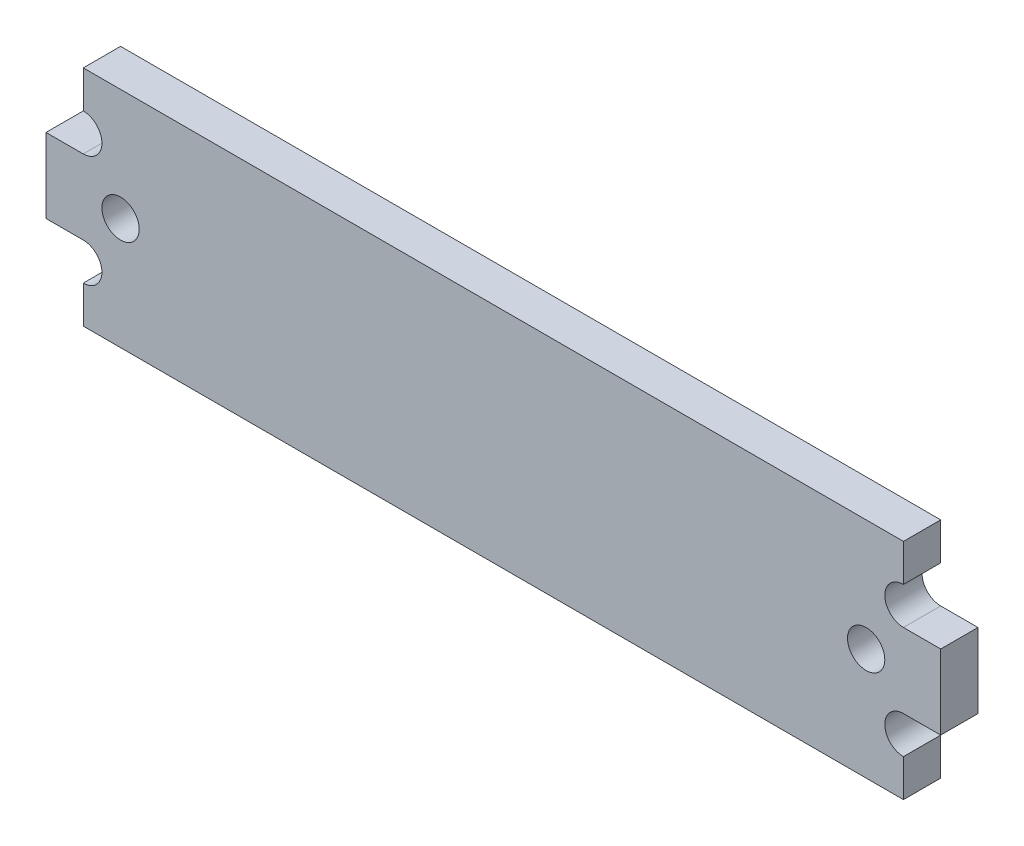
SolidWorks part; units mm, degrees
material "自訂玻璃纖維"
ref_plane "前基準面" through (0, 0, 0) normal (0, 0, 1) x (1, 0, 0)
ref_plane "上基準面" through (0, 0, 0) normal (0, 1, 0) x (1, 0, 0)
ref_plane "右基準面" through (0, 0, 0) normal (1, 0, 0) x (0, 0, -1)
sketch "草圖1" plane through (0, 0, 0) normal (0, 0, 1) x (1, 0, 0)
  line L0 (-31.3907, -5.425) -> (-31.3907, -7.425)
  line L1 (-31.3907, 4.575) -> (12.6093, 4.575)
  line L2 (-31.3907, 4.575) -> (-31.3907, 2.575)
  line L3 (-31.3907, -7.425) -> (12.6093, -7.425)
  line L4 (12.6093, 4.575) -> (12.6093, 2.575)
  line L5 (-31.3907, 0.575) -> (-33.3907, 0.575)
  line L6 (12.6093, -5.425) -> (12.6093, -7.425)
  line L7 (-31.3907, -3.425) -> (-33.3907, -3.425)
  line L8 (-33.3907, 0.575) -> (-33.3907, -3.425)
  line L9 (14.6093, 0.575) -> (14.6093, -3.425)
  line L10 (12.6093, -3.425) -> (14.6093, -3.425)
  line L11 (12.6093, 0.575) -> (14.6093, 0.575)
  arc A0 (-31.3907, 0.575) -> (-31.3907, 2.575) centre (-31.3907, 1.575) ccw
  arc A1 (-31.3907, -3.425) -> (-31.3907, -5.425) centre (-31.3907, -4.425) cw
  arc A2 (12.6093, -3.425) -> (12.6093, -5.425) centre (12.6093, -4.425) ccw
  arc A3 (12.6093, 0.575) -> (12.6093, 2.575) centre (12.6093, 1.575) cw
  circle A4 centre (-29.3907, -1.425) radius 1
  circle A5 centre (10.6093, -1.425) radius 1
  point P6 (12.6093, 4.575)
  point P11 (-31.3907, -7.425)
  point P14 (-31.3907, 4.575)
  point P19 (-31.3907, 4.575)
  point P20 (12.6093, -7.425)
  dimension "D3" = 2
  dimension "D4" = 4
  dimension "D5" = 2
  dimension "D6" = 2
  dimension "D1" = 12
  dimension "D2" = 44
extrude "填料-伸長1" add sketch "草圖1" along normal blind 2
